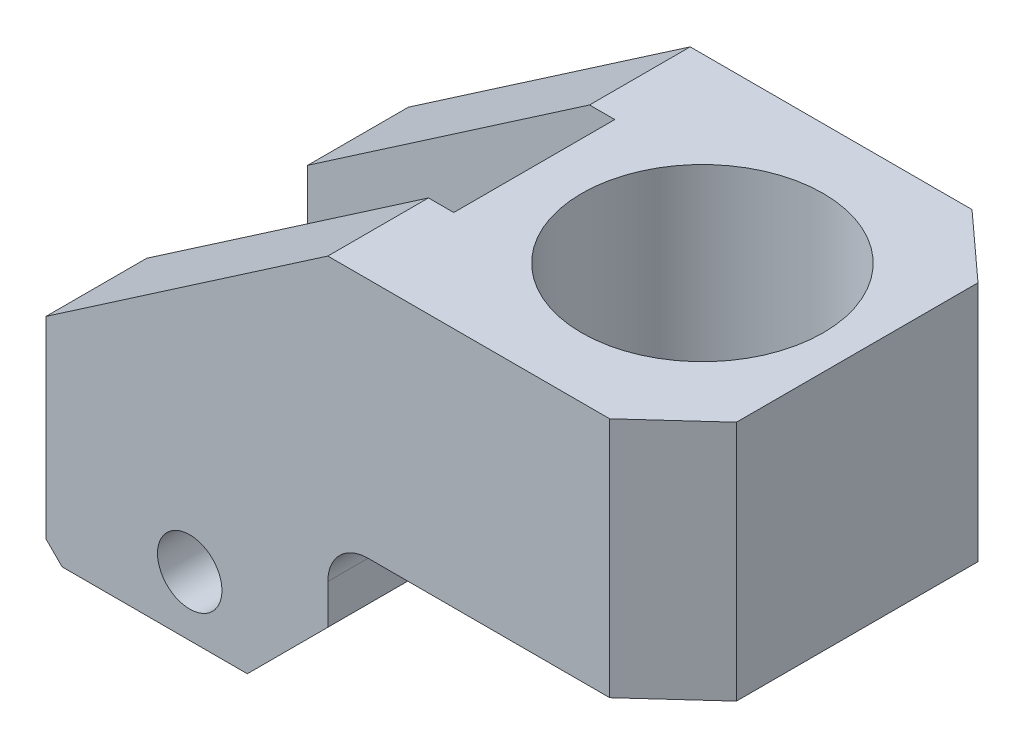
SolidWorks part; units mm, degrees
ref_plane "Спереди" through (0, 0, 0) normal (0, 0, 1) x (1, 0, 0)
ref_plane "Сверху" through (0, 0, 0) normal (0, 1, 0) x (1, 0, 0)
ref_plane "Справа" through (0, 0, 0) normal (1, 0, 0) x (0, 0, -1)
sketch "Эскиз1" plane through (0, 0, 0) normal (0, 1, 0) x (1, 0, 0)
  line L0 (-8.5273, 0) -> (45.8432, 0) construction
  line L1 (-24.0191, 22.5) -> (10.9809, 22.5)
  line L2 (-24.0191, 22.5) -> (-24.0191, -22.5)
  line L3 (-24.0191, -22.5) -> (10.9809, -22.5)
  line L4 (19.2235, 15) -> (19.2235, -15)
  line L7 (10.9809, -22.5) -> (19.2235, -15)
  line L8 (10.9809, 22.5) -> (19.2235, 15)
extrude "Вытянуть1" add sketch "Эскиз1" along normal blind 30
sketch "Эскиз2" plane through (0, 30, 0) normal (0, 1, 0) x (1, 0, 0)
  circle A0 centre (0, 0) radius 15
extrude "Вытянуть2" cut sketch "Эскиз2" against normal through all
sketch "Эскиз6" plane through (0, 0, -22.5) normal (0, 0, -1) x (-1, 0, 0)
  line L0 (24.0191, -19.9275) -> (24.0191, 30)
  line L2 (59.0191, -19.9275) -> (59.0191, 6.0126)
  line L3 (59.0191, -19.9275) -> (24.0191, -19.9275)
  line L4 (24.0191, 30) -> (59.0191, 6.0126)
extrude "Вытянуть3" add sketch "Эскиз6" against normal up to vertex (45 mm away) up to point (-24.0191, 30, 22.5)
sketch "Эскиз3" plane through (0, 30, 0) normal (0, 1, 0) x (1, 0, 0)
  line L0 (-38.6818, 0) -> (-47.6939, 0) construction
  line L3 (-65.5391, 10) -> (-20.8824, 10)
  line L4 (-65.5391, 10) -> (-65.5391, -10)
  line L5 (-65.5391, -10) -> (-20.8824, -10)
  line L6 (-20.8824, 10) -> (-20.8824, -10)
  line L7 (-65.5391, 10) -> (-20.8824, -10) construction
  line L8 (-65.5391, -10) -> (-20.8824, 10) construction
  point P1 (-43.2108, 0)
extrude "Вырез-Вытянуть1" cut sketch "Эскиз3" against normal blind 130 from offset 70
sketch "Эскиз7" plane through (0, 0, -22.5) normal (0, 0, -1) x (-1, 0, 0)
  circle A0 centre (41.1705, -12.5474) radius 4
extrude "Вырез-Вытянуть2" cut sketch "Эскиз7" against normal through all
fillet "Скругление1" radius 5 1 edges
chamfer "Фаска5" distance 2 angle 45 2 edges at (-59.0191, -19.9275, -16.25) (-59.0191, -19.9275, 16.25)
chamfer "Фаска6" distance 10 angle 45 2 edges at (-24.0191, -19.9275, -16.25) (-24.0191, -19.9275, 16.25)
